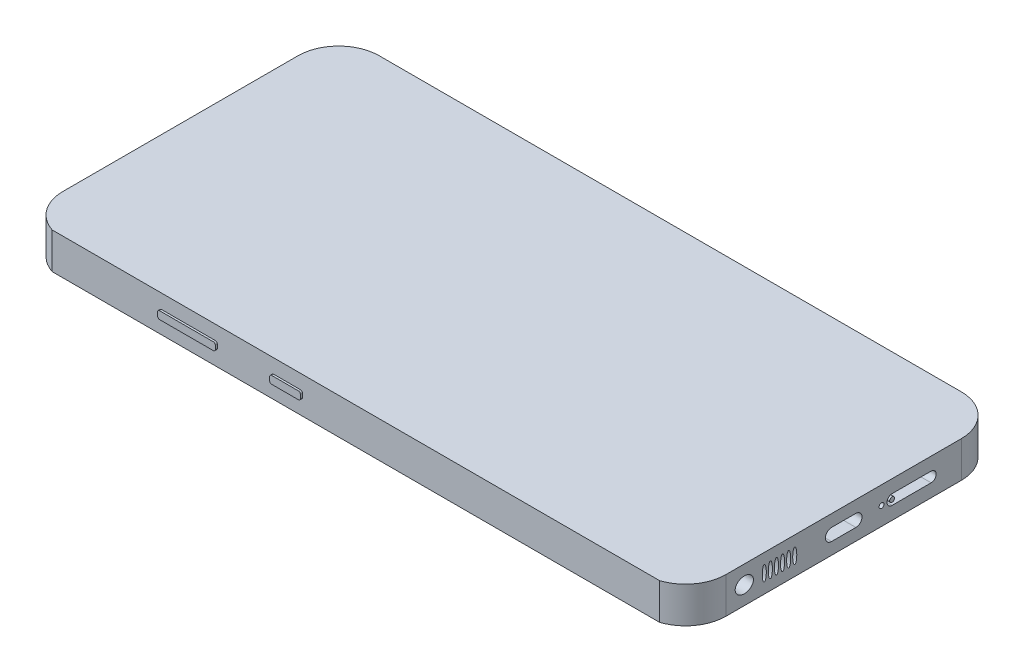
SolidWorks part; units mm, degrees
ref_plane "前视基准面" through (0, 0, 0) normal (0, 0, 1) x (1, 0, 0)
ref_plane "上视基准面" through (0, 0, 0) normal (0, 1, 0) x (1, 0, 0)
ref_plane "右视基准面" through (0, 0, 0) normal (1, 0, 0) x (0, 0, -1)
other "Configuration Table"
sketch "草图1" plane through (0, 0, 0) normal (0, 1, 0) x (1, 0, 0)
  line L1 (10, 0) -> (153.3, 0)
  line L2 (0, 10) -> (0, 67.9)
  line L3 (10, 77.9) -> (153.3, 77.9)
  line L4 (163.3, 10) -> (163.3, 67.9)
  arc A0 (153.3, 77.9) -> (163.3, 67.9) centre (153.3, 67.9) cw
  arc A1 (153.3, 0) -> (163.3, 10) centre (153.3, 10) ccw
  arc A2 (10, 0) -> (0, 10) centre (10, 10) cw
  arc A3 (0, 67.9) -> (10, 77.9) centre (10, 67.9) cw
  point P7 (163.3, 77.9)
  point P12 (0, 0)
  point P15 (0, 77.9)
  dimension "D3" = 10
  dimension "D1" = 77.9
  dimension "D2" = 163.3
extrude "凸台-拉伸1" add sketch "草图1" along normal blind 8.9
sketch "草图2" plane through (0, 0, 0) normal (1, 0, 0) x (0, 0, -1)
  line L0 (10, 4.45) -> (34.45, 4.45) construction
  line L1 (10, 8.9) -> (10, 0) construction
  line L2 (67.9, 8.9) -> (67.9, 0) construction
  line L3 (38.95, 8.9) -> (38.95, 5.95) construction
  line L4 (10, 8.9) -> (67.9, 8.9) construction
  line L5 (10, 0) -> (67.9, 0) construction
  line L7 (41.95, 2.95) -> (35.95, 2.95)
  line L9 (41.95, 5.95) -> (35.95, 5.95)
  line L11 (60.4785, 3.2) -> (50.8715, 3.2)
  line L13 (38.95, 2.95) -> (38.95, 0) construction
  line L14 (60.4785, 5.7) -> (50.8715, 5.7)
  line L15 (43.45, 4.45) -> (50.8715, 4.45) construction
  line L19 (61.7285, 4.45) -> (67.9, 4.45) construction
  arc A0 (35.95, 5.95) -> (35.95, 2.95) centre (35.95, 4.45) ccw
  arc A1 (41.95, 2.95) -> (41.95, 5.95) centre (41.95, 4.45) ccw
  arc A2 (50.8715, 5.7) -> (50.8715, 3.2) centre (50.8715, 4.45) ccw
  arc A3 (60.4785, 3.2) -> (60.4785, 5.7) centre (60.4785, 4.45) ccw
  circle A4 centre (50.8715, 4.45) radius 0.6
  circle A5 centre (48.2725, 4.45) radius 0.6
  ellipse E0 centre (14.4854, 4.45) end of major axis (12.2354, 4.45) minor radius 1.9
  ellipse E1 centre (19.3993, 4.45) end of major axis (19.3993, 6.35) minor radius 0.5
  ellipse E2 centre (20.8993, 4.45) end of major axis (20.8993, 6.35) minor radius 0.5
  ellipse E3 centre (22.3993, 4.45) end of major axis (22.3993, 6.35) minor radius 0.5
  ellipse E4 centre (23.8993, 4.45) end of major axis (23.8993, 6.35) minor radius 0.5
  ellipse E5 centre (25.3993, 4.45) end of major axis (25.3993, 6.35) minor radius 0.5
  ellipse E6 centre (26.8993, 4.45) end of major axis (26.8993, 6.35) minor radius 0.5
  point P12 (38.95, 4.45)
  point P18 (14.4854, 4.45)
  point P21 (19.3993, 4.45)
  point P37 (20.8993, 4.45)
  point P44 (22.3993, 4.45)
  point P51 (23.8993, 4.45)
  point P58 (25.3993, 4.45)
  point P65 (26.8993, 4.45)
  point P74 (55.675, 4.45)
  dimension "D9" = 1.2
  dimension "D10" = 1.2
  dimension "D1" = 6
  dimension "D2" = 3
  dimension "D3" = 4.5
  dimension "D4" = 3.8
  dimension "D5" = 1
  dimension "D6" = 3.8
  dimension "D8" = 2.5
  dimension "D7" = 6
extrude "切除-拉伸5" cut sketch "草图2" against normal blind 8.9 from surface at 163.3 starting at face at (163.3, 4.45, -38.95)
sketch "草图7" plane through (0, 0, 0) normal (0, 0, 1) x (1, 0, 0)
  line L0 (10, 4.45) -> (153.3, 4.45) construction
  line L1 (10, 8.9) -> (10, 0) construction
  line L2 (153.3, 8.9) -> (153.3, 0) construction
  line L4 (33.8265, 3.503) -> (47.0393, 3.503)
  line L5 (33.3265, 4.003) -> (33.3265, 4.897)
  line L6 (33.8265, 5.397) -> (47.0393, 5.397)
  line L7 (47.5393, 4.003) -> (47.5393, 4.897)
  line L8 (33.3265, 3.503) -> (47.5393, 5.397) construction
  line L9 (33.3265, 5.397) -> (47.5393, 3.503) construction
  line L10 (61.423, 3.503) -> (68.0032, 3.503)
  line L11 (60.923, 4.003) -> (60.923, 4.897)
  line L12 (61.423, 5.397) -> (68.0032, 5.397)
  line L13 (68.5032, 4.003) -> (68.5032, 4.897)
  line L14 (60.923, 3.503) -> (68.5032, 5.397) construction
  line L15 (60.923, 5.397) -> (68.5032, 3.503) construction
  arc A0 (68.0032, 3.503) -> (68.5032, 4.003) centre (68.0032, 4.003) ccw
  arc A1 (68.0032, 5.397) -> (68.5032, 4.897) centre (68.0032, 4.897) cw
  arc A2 (60.923, 4.897) -> (61.423, 5.397) centre (61.423, 4.897) cw
  arc A3 (61.423, 3.503) -> (60.923, 4.003) centre (61.423, 4.003) cw
  arc A4 (47.0393, 3.503) -> (47.5393, 4.003) centre (47.0393, 4.003) ccw
  arc A5 (47.0393, 5.397) -> (47.5393, 4.897) centre (47.0393, 4.897) cw
  arc A6 (33.8265, 3.503) -> (33.3265, 4.003) centre (33.8265, 4.003) cw
  arc A7 (33.3265, 4.897) -> (33.8265, 5.397) centre (33.8265, 4.897) cw
  point P6 (40.4329, 4.45)
  point P11 (64.7131, 4.45)
  dimension "D1" = 0.5
extrude "切除-拉伸6" cut sketch "草图7" against normal blind 0.5 flip side to cut
sketch "草图8" plane through (0, 0, 0) normal (0, -1, 0) x (1, 0, 0)
  line L2 (0, 0) -> (0, -77.9)
  line L8 (1.4653, -67.9) -> (1.4653, -10)
  line L9 (10, -76.4347) -> (153.3, -76.4347)
  line L10 (161.8347, -67.9) -> (161.8347, -10)
  line L11 (153.3, -1.4653) -> (10, -1.4653)
  arc A0 (1.5, -76.9) -> (1, -76.4) centre (1.5, -76.4) cw
  arc A1 (1.5, -1) -> (1, -1.5) centre (1.5, -1.5) ccw
  arc A2 (162.3, -1.5) -> (161.8, -1) centre (161.8, -1.5) ccw
  arc A3 (161.8, -76.9) -> (162.3, -76.4) centre (161.8, -76.4) ccw
  arc A4 (1.4653, -67.9) -> (10, -76.4347) centre (10, -67.9) ccw
  arc A5 (10, -1.4653) -> (1.4653, -10) centre (10, -10) ccw
  arc A6 (153.3, -76.4347) -> (161.8347, -67.9) centre (153.3, -67.9) ccw
  arc A7 (161.8347, -10) -> (153.3, -1.4653) centre (153.3, -10) ccw
  dimension "D4" = 0.5
  dimension "D2" = 77.9
extrude "切除-拉伸7" cut sketch "草图8" against normal blind 0.5 contours A6 L10 A7 L11 A5 L8 A4 L9
